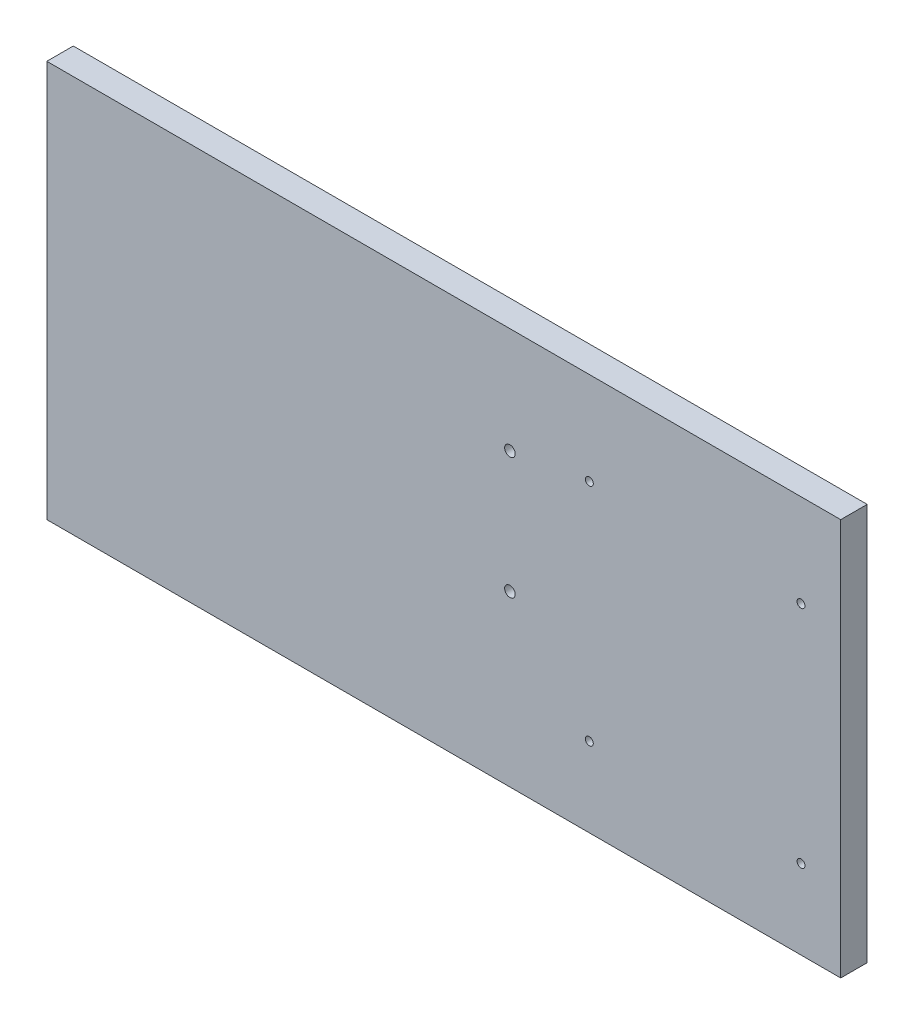
SolidWorks part; units mm, degrees
material "Faia"
ref_plane "Plano frontal" through (0, 0, 0) normal (0, 0, 1) x (1, 0, 0)
ref_plane "Plano superior" through (0, 0, 0) normal (0, 1, 0) x (1, 0, 0)
ref_plane "Plano direito" through (0, 0, 0) normal (1, 0, 0) x (0, 0, -1)
sketch "Esboço1" plane through (0, 0, 0) normal (0, 0, 1) x (1, 0, 0)
  line L0 (150, 0) -> (-150, 0) construction
  line L1 (-150, 75) -> (150, 75)
  line L2 (-150, 75) -> (-150, -75)
  line L3 (-150, -75) -> (150, -75)
  line L4 (150, 75) -> (150, -75)
  line L5 (-150, 75) -> (150, -75) construction
  line L6 (-150, -75) -> (150, 75) construction
  line L7 (70, 0) -> (-230, 0) construction
  line L8 (25, -11) -> (25, 35) construction
  line L9 (55, 40) -> (55, -45) construction
  line L10 (135, 40) -> (55, 40) construction
  circle A0 centre (135, 40) radius 1.5
  circle A1 centre (135, -45) radius 1.5
  circle A2 centre (55, -45) radius 1.5
  circle A3 centre (55, 40) radius 1.5
  circle A4 centre (25, 35) radius 2
  circle A5 centre (25, -11) radius 2
  point P0 (0, 0)
  point P21 (5, 0)
  dimension "D5" = 3
  dimension "D8" = 4
  dimension "D1" = 300
  dimension "D2" = 150
  dimension "D3" = 15
  dimension "D4" = 85
  dimension "D7" = 80
  dimension "D9" = 46
  dimension "D10" = 125
  dimension "D11" = 40
  dimension "D12" = 5
  dimension "D6" = 2
extrude "Ressalto-extrusão1" add sketch "Esboço1" along normal blind 10 contours L4 L1 L2 L3 A3 A1 A0 A2
